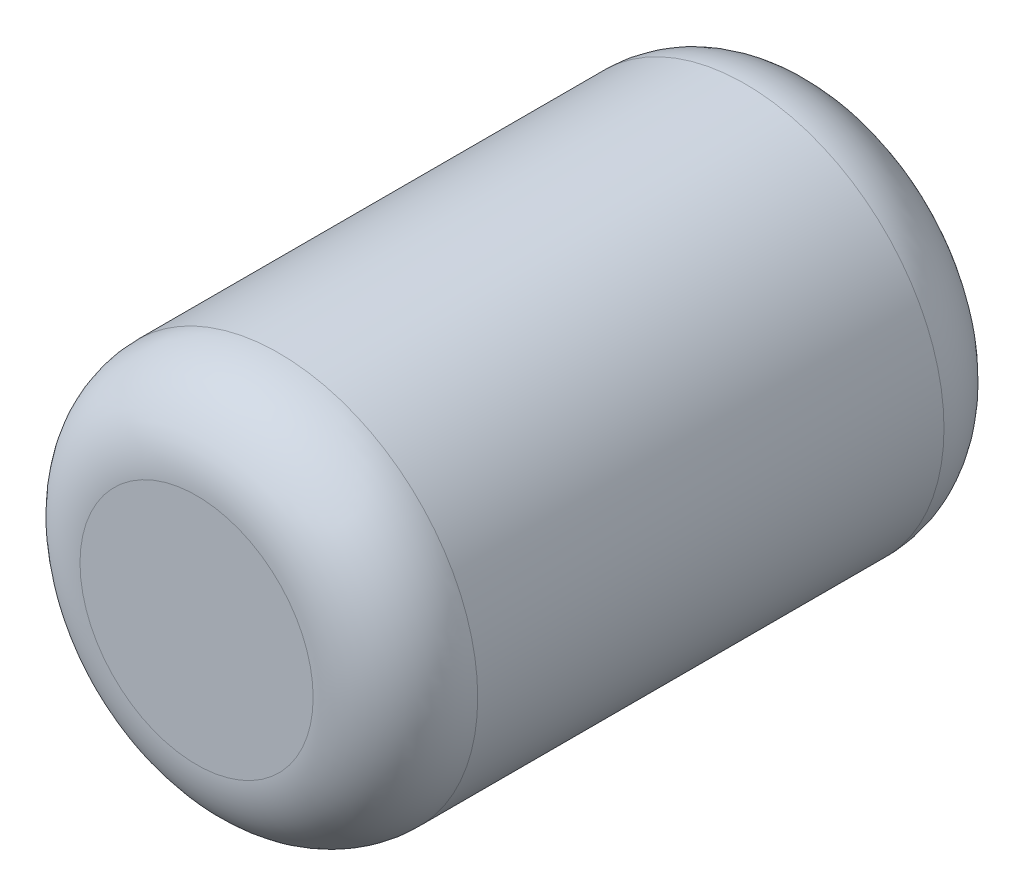
SolidWorks part; units mm, degrees
ref_plane "Front Plane" through (0, 0, 0) normal (0, 0, 1) x (1, 0, 0)
ref_plane "Top Plane" through (0, 0, 0) normal (0, 1, 0) x (1, 0, 0)
ref_plane "Right Plane" through (0, 0, 0) normal (1, 0, 0) x (0, 0, -1)
sketch "Sketch2" plane through (0, 0, 0) normal (0, 0, 1) x (1, 0, 0)
  circle A0 centre (0, 0) radius 7.25
  dimension "D1" = 14.5
extrude "Boss-Extrude1" add sketch "Sketch2" along normal blind 23
ref_point "Point1"
ref_point "Point2"
fillet "Fillet1" radius 3 2 edges at (7.25, 0, 23) (7.25, 0, 0)
